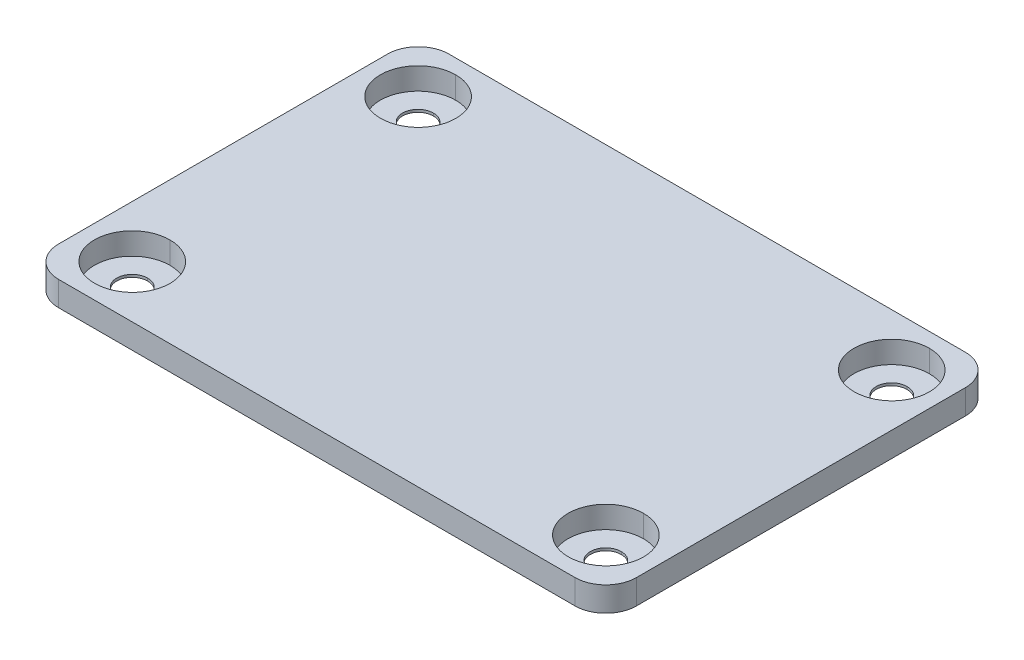
SolidWorks part; units mm, degrees
ref_plane "Front Plane" through (0, 0, 0) normal (0, 0, 1) x (1, 0, 0)
ref_plane "Top Plane" through (0, 0, 0) normal (0, 1, 0) x (1, 0, 0)
ref_plane "Right Plane" through (0, 0, 0) normal (1, 0, 0) x (0, 0, -1)
sketch "Sketch1" plane through (0, 0, 0) normal (0, 1, 0) x (1, 0, 0)
  line L1 (-34.7968, 56.2829) -> (59.2032, 56.2829)
  line L2 (-34.7968, 56.2829) -> (-34.7968, -7.2171)
  line L3 (-34.7968, -7.2171) -> (59.2032, -7.2171)
  line L4 (59.2032, 56.2829) -> (59.2032, -7.2171)
extrude "Boss-Extrude1" add sketch "Sketch1" along normal blind 4
sketch "Sketch2" plane through (0, 0, 0) normal (0, -1, 0) x (1, 0, 0)
  line L0 (-26.2968, -1.2829) -> (-26.2968, -47.7829) construction
  line L1 (-26.2968, -47.7829) -> (50.7032, -47.7829) construction
  line L2 (50.7032, -47.7829) -> (50.7032, -1.2829) construction
  line L3 (-26.2968, -1.2829) -> (50.7032, -1.2829) construction
  line L4 (-34.7968, 7.2171) -> (59.2032, 7.2171) construction
  line L5 (59.2032, -56.2829) -> (-34.7968, -56.2829) construction
  line L6 (-34.7968, -56.2829) -> (-34.7968, 7.2171) construction
  line L8 (12.2032, 7.2171) -> (12.2032, -56.2829) construction
  line L9 (0, -24.5329) -> (177.3966, -24.5329) construction
  circle A0 centre (-26.2968, -1.2829) radius 2.5
  circle A1 centre (50.7532, -1.2829) radius 2.5
  circle A4 centre (50.7532, -47.7829) radius 2.5
  circle A5 centre (-26.2968, -47.7829) radius 2.5
  circle A6 centre (50.7032, -1.2829) radius 2.5
  circle A7 centre (50.7032, -47.7829) radius 2.5
  circle A8 centre (-26.3468, -47.7829) radius 2.5
  circle A9 centre (-26.3468, -1.2829) radius 2.5
  dimension "D5" = 77.05
  dimension "D1" = 8.5
  dimension "D2" = 8.5
  dimension "D3" = 8.5
hole_wizard "CBORE SLOT for M5 Hex Head Bolt1" positions "Sketch6" profile "Sketch7" size "M5" standard "ANSI Metric" slot yes
sketch "Sketch6" plane through (0, 4, 0) normal (0, 1, 0) x (1, 0, 0)
  point P0 (-26.2968, 47.7829)
  point P3 (-26.2968, 1.2829)
  point P6 (50.7532, 47.7829)
  point P9 (50.7532, 1.2829)
  point P19 (-26.3468, 47.7829)
  point P22 (-26.3468, 1.2829)
  point P25 (50.7032, 1.2829)
  point P28 (50.7032, 47.7829)
sketch "Sketch7" plane through (-26.2968, 4, -47.7829) normal (1, 0, 0) x (0, 0, 1)
  line L0 (0, 0) -> (0, 19.5022)
  line L1 (0, 19.5022) -> (2.5, 18)
  line L2 (2.5, 18) -> (2.5, 3.58)
  line L3 (2.5, 3.58) -> (6.12, 3.58)
  line L4 (6.12, 3.58) -> (6.12, 0)
  line L5 (6.12, 0) -> (0, 0)
  line L10 (0, 19.5022) -> (-2.5, 18) construction
  line L11 (0, -6.35) -> (0, 107.95) construction
  dimension "Hole Dia." = 5
  dimension "Hole Depth" = 18
  dimension "C'Bore Dia." = 12.24
  dimension "C'Bore Depth" = 3.58
  dimension "Drill Angle" = 118
fillet "Fillet1" radius 5 4 edges at (59.2032, 2, 7.2171) (59.2032, 2, -56.2829) (-34.7968, 2, 7.2171) (-34.7968, 2, -56.2829)
